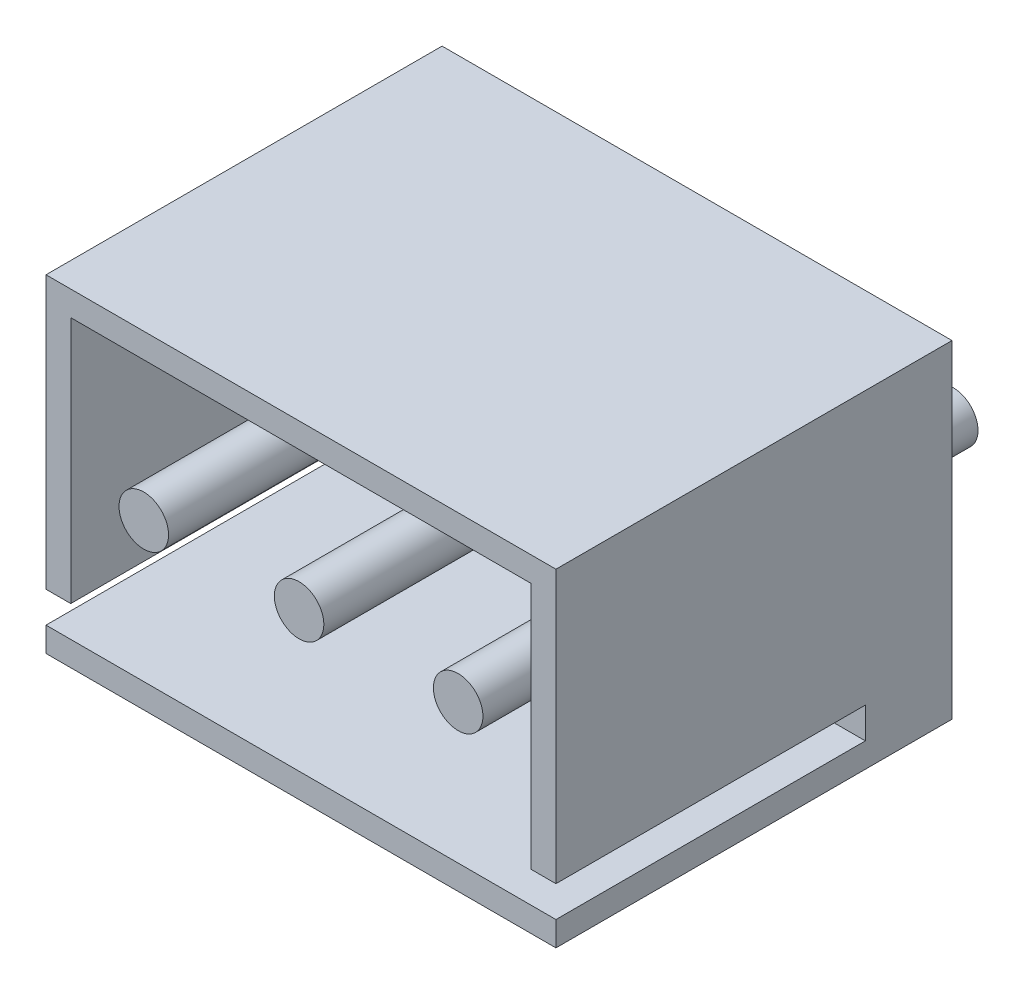
SolidWorks part; units mm, degrees
ref_plane "Спереди" through (0, 0, 0) normal (0, 0, 1) x (1, 0, 0)
ref_plane "Сверху" through (0, 0, 0) normal (0, 1, 0) x (1, 0, 0)
ref_plane "Справа" through (0, 0, 0) normal (1, 0, 0) x (0, 0, -1)
sketch "Эскиз1" plane through (0, 0, 0) normal (0, 0, 1) x (1, 0, 0)
  line L0 (0, 43.0382) -> (0, -41.0882) construction
  line L1 (-52.7879, 0) -> (56.1307, 0) construction
  line L3 (-4.12, 2.65) -> (4.12, 2.65)
  line L4 (-4.12, 2.65) -> (-4.12, -2.65)
  line L5 (-4.12, -2.65) -> (4.12, -2.65)
  line L6 (4.12, 2.65) -> (4.12, -2.65)
  dimension "D1" = 8.24
  dimension "D2" = 5.3
extrude "Вытянуть1" add sketch "Эскиз1" along normal blind 6.4
sketch "Эскиз2" plane through (0, 0, 6.4) normal (0, 0, 1) x (1, 0, 0)
  line L14 (-3.347, 0) -> (3.2862, 0) construction
  line L15 (0, 1.6982) -> (0, -0.832) construction
  line L18 (-3.72, -2.25) -> (3.72, -2.25)
  line L19 (3.72, -2.25) -> (3.72, 2.25)
  line L20 (3.72, 2.25) -> (-3.72, 2.25)
  line L21 (-3.72, 2.25) -> (-3.72, -2.25)
  line L22 (-3.72, -2.25) -> (3.72, -2.25)
  line L23 (3.72, -2.25) -> (3.72, 2.25)
  line L24 (3.72, 2.25) -> (-3.72, 2.25)
  line L25 (-3.72, 2.25) -> (-3.72, -2.25)
  circle A0 centre (-2.54, 0) radius 0.4
  circle A1 centre (2.54, 0) radius 0.4
  circle A2 centre (-0.0304, 0) radius 0.4
  dimension "D2" = 5.08
  dimension "D3" = 0.8
  dimension "D1" = 0.4
extrude "Вырез-Вытянуть1" cut sketch "Эскиз2" against normal blind 5
sketch "Эскиз3" plane through (0, 0, 6.4) normal (0, 0, 1) x (1, 0, 0)
  line L1 (-4.8996, -2.2528) -> (4.7987, -2.2528)
  line L2 (-4.8996, -2.2528) -> (-4.8996, -1.7514)
  line L3 (-4.8996, -1.7514) -> (4.7987, -1.7514)
  line L4 (4.7987, -2.2528) -> (4.7987, -1.7514)
extrude "Вырез-Вытянуть2" cut sketch "Эскиз3" against normal up to surface (5 mm away) up to face at (0.3696, 0, 1.4)
sketch "Эскиз4" plane through (0, 0, 6.4) normal (0, 0, 1) x (1, 0, 0)
  circle A1 centre (-2.54, 0) radius 0.4
  circle A2 centre (-2.54, 0) radius 0.4
  circle A3 centre (2.54, 0) radius 0.4
  circle A4 centre (2.54, 0) radius 0.4
  circle A5 centre (-0.0304, 0) radius 0.4
  circle A6 centre (-0.0304, 0) radius 0.4
  dimension "D1" = 0
  dimension "D2" = 0
  dimension "D3" = 0
extrude "Вытянуть2" add sketch "Эскиз4" against normal blind 8
